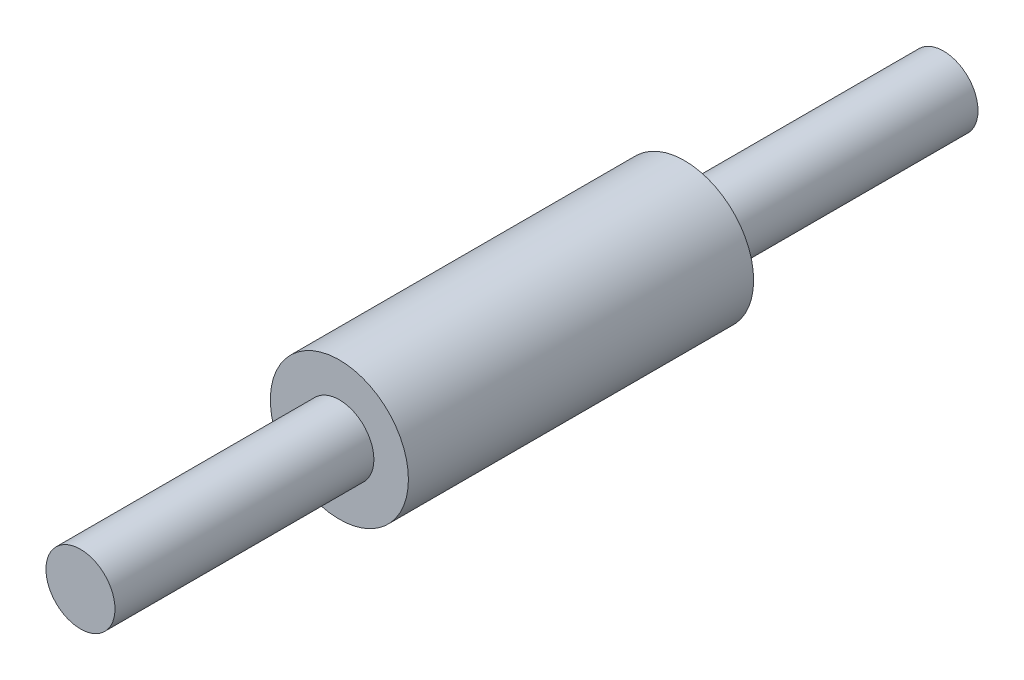
SolidWorks part; units mm, degrees
ref_plane "Plan de face" through (0, 0, 0) normal (0, 0, 1) x (1, 0, 0)
ref_plane "Plan de dessus" through (0, 0, 0) normal (0, 1, 0) x (1, 0, 0)
ref_plane "Plan de droite" through (0, 0, 0) normal (1, 0, 0) x (0, 0, -1)
sketch "Esquisse2" plane through (0, 0, 0) normal (0, 1, 0) x (1, 0, 0)
  line L0 (-10, 125) -> (-10, 50)
  line L1 (-10, 50) -> (-20, 50)
  line L2 (-20, 50) -> (-20, -50)
  line L3 (-20, -50) -> (-10, -50)
  line L4 (-10, -50) -> (-10, -125)
  line L5 (-10, -125) -> (0, -125)
  line L6 (0, -125) -> (0, 125)
  line L7 (0, 125) -> (-10, 125)
  line L8 (-25.3158, 0) -> (25.7173, 0) construction
  point P11 (0, 0)
  point P12 (0, 0)
  dimension "D1" = 250
  dimension "D2" = 100
  dimension "D3" = 10
  dimension "D4" = 20
revolve "Révolution1" add sketch "Esquisse2" angle 360 about L6
